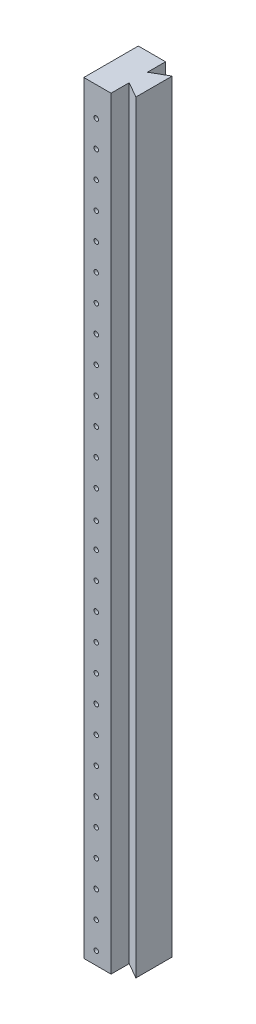
SolidWorks part; units mm, degrees
ref_plane "Front Plane" through (0, 0, 0) normal (0, 0, 1) x (1, 0, 0)
ref_plane "Top Plane" through (0, 0, 0) normal (0, 1, 0) x (1, 0, 0)
ref_plane "Right Plane" through (0, 0, 0) normal (1, 0, 0) x (0, 0, -1)
sketch "Sketch1" plane through (0, 0, 0) normal (0, 1, 0) x (1, 0, 0)
  line L0 (-24.6766, 0) -> (-24.6766, -25.4)
  line L1 (-24.6766, 0) -> (-11.9766, 0)
  line L2 (-11.9766, 0) -> (-11.9766, -8.4667)
  line L3 (-11.9766, -25.4) -> (-24.6766, -25.4)
  line L4 (-11.9766, -8.4667) -> (-4.6442, -4.2333)
  line L5 (-11.9766, -25.4) -> (-11.9766, -16.9333)
  line L6 (-11.9766, -16.9333) -> (-4.6442, -21.1667)
  line L7 (-4.6442, -4.2333) -> (-4.6442, -21.1667)
  dimension "D1" = 25.4
  dimension "D2" = 8.4667
  dimension "D3" = 8.4667
  dimension "D4" = 16.9333
  dimension "D5" = 8.4667
  dimension "D6" = 12.7
  dimension "D7" = 12.7
  dimension "D8" = 8.4667
extrude "Boss-Extrude1" add sketch "Sketch1" along normal blind 355.6 contours L1 L2 L4 L7 L6 L5 L3 L0
sketch "Sketch2" plane through (0, 0, 0) normal (0, 0, -1) x (-1, 0, 0)
  circle A0 centre (18.8792, 329.6265) radius 1.85
  circle A1 centre (18.8792, 341.9565) radius 1.8415
  circle A2 centre (18.8792, 317.1805) radius 1.85
  circle A3 centre (18.8792, 304.7345) radius 1.85
  circle A4 centre (18.8792, 292.2885) radius 1.85
  circle A5 centre (18.8792, 279.8425) radius 1.85
  circle A6 centre (18.8792, 267.3965) radius 1.85
  circle A7 centre (18.8792, 254.9505) radius 1.85
  circle A8 centre (18.8792, 242.5045) radius 1.85
  circle A9 centre (18.8792, 230.0585) radius 1.85
  circle A10 centre (18.8792, 217.6125) radius 1.85
  circle A11 centre (18.8792, 205.1665) radius 1.85
  circle A12 centre (18.8792, 192.7205) radius 1.85
  circle A13 centre (18.8792, 180.2745) radius 1.85
  circle A14 centre (18.8792, 167.8285) radius 1.85
  circle A15 centre (18.8792, 155.3825) radius 1.85
  circle A16 centre (18.8792, 142.9365) radius 1.85
  circle A17 centre (18.8792, 130.4905) radius 1.85
  circle A18 centre (18.8792, 118.0445) radius 1.85
  circle A19 centre (18.8792, 105.5985) radius 1.85
  circle A20 centre (18.8792, 93.1525) radius 1.85
  circle A21 centre (18.8792, 80.7065) radius 1.85
  circle A22 centre (18.8792, 68.2605) radius 1.85
  circle A23 centre (18.8792, 55.8145) radius 1.85
  circle A24 centre (18.8792, 43.3685) radius 1.85
  circle A25 centre (18.8792, 30.9225) radius 1.85
  circle A26 centre (18.8792, 18.4765) radius 1.85
  circle A27 centre (18.8792, 6.0305) radius 1.85
  dimension "D1" = 3.7
  dimension "D2" = 3.683
  dimension "D3" = 12.33
  dimension "D5" = 12.446
  dimension "D4" = 27
hole_wizard "#27 (0.144) Diameter Hole1" positions "Sketch4" profile "Sketch5" hole size "#27" standard "ANSI Inch" end condition through all
sketch "Sketch4" plane through (0, 0, 0) normal (0, 0, -1) x (-1, 0, 0)
  point P0 (18.8792, 341.9565)
  point P3 (18.8792, 329.6265)
  point P6 (18.8792, 317.1805)
  point P9 (18.8792, 304.7345)
  point P12 (18.8792, 292.2885)
  point P15 (18.8792, 279.8425)
  point P18 (18.8792, 267.3965)
  point P21 (18.8792, 254.9505)
  point P24 (18.8792, 242.5045)
  point P27 (18.8792, 230.0585)
  point P30 (18.8792, 217.6125)
  point P33 (18.8792, 205.1665)
  point P36 (18.8792, 192.7205)
  point P39 (18.8792, 179.5888)
  point P41 (18.8792, 167.8285)
  point P44 (18.8792, 155.3825)
  point P47 (18.8792, 142.9365)
  point P50 (18.8792, 130.4905)
  point P53 (18.8792, 118.0445)
  point P56 (18.8792, 105.5985)
  point P59 (18.8792, 93.1525)
  point P62 (18.8792, 80.7065)
  point P66 (18.8792, 68.2605)
  point P69 (18.8792, 55.8145)
  point P72 (18.8792, 43.3685)
  point P75 (18.8792, 30.9225)
  point P78 (18.8792, 18.4765)
  point P81 (18.8792, 6.0305)
sketch "Sketch5" plane through (-18.8792, 341.9565, 0) normal (1, 0, 0) x (0, 1, 0)
  line L0 (0, 0) -> (0, 25.4)
  line L1 (0, 25.4) -> (1.05, 25.4)
  line L2 (1.05, 25.4) -> (1.05, 0)
  line L5 (1.05, 0) -> (0, 0)
  line L11 (0, -6.35) -> (0, 107.95) construction
  dimension "Thru Hole Dia." = 2.1
  dimension "Thru Hole Depth" = 25.4
